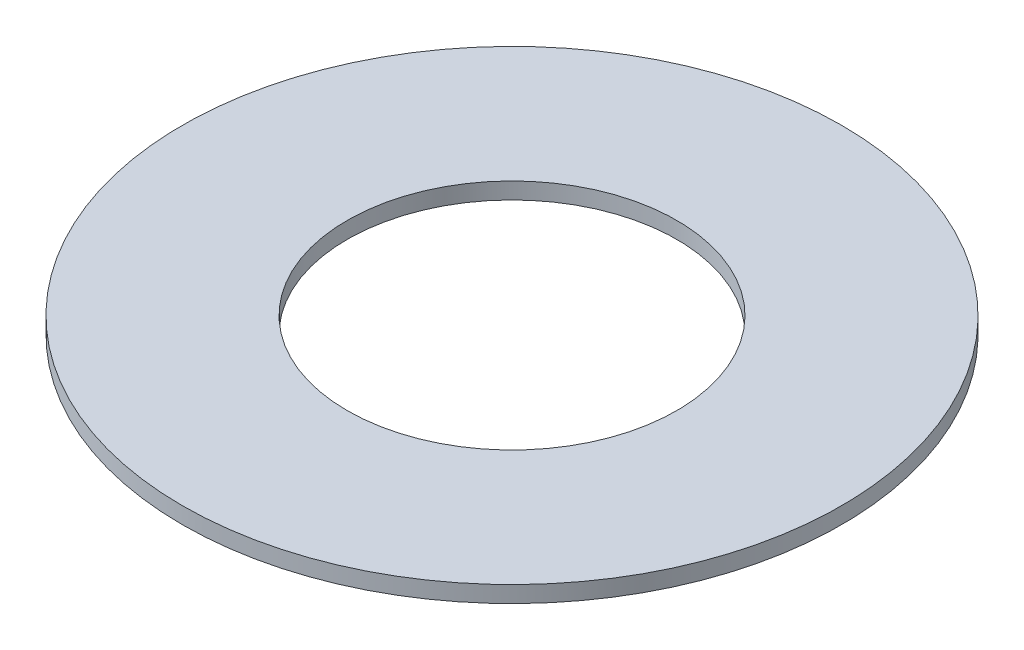
SolidWorks part; units mm, degrees
material "AISI 1020"
ref_plane "Plano frontal" through (0, 0, 0) normal (0, 0, 1) x (1, 0, 0)
ref_plane "Plano superior" through (0, 0, 0) normal (0, 1, 0) x (1, 0, 0)
ref_plane "Plano direito" through (0, 0, 0) normal (1, 0, 0) x (0, 0, -1)
sketch "Esboço1" plane through (0, 0, 0) normal (0, 1, 0) x (1, 0, 0)
  circle A0 centre (0, 0) radius 5
  circle A1 centre (0, 0) radius 10
  dimension "D1" = 20
  dimension "D2" = 10
extrude "Ressalto-extrusão1" add sketch "Esboço1" along normal blind 0.5
